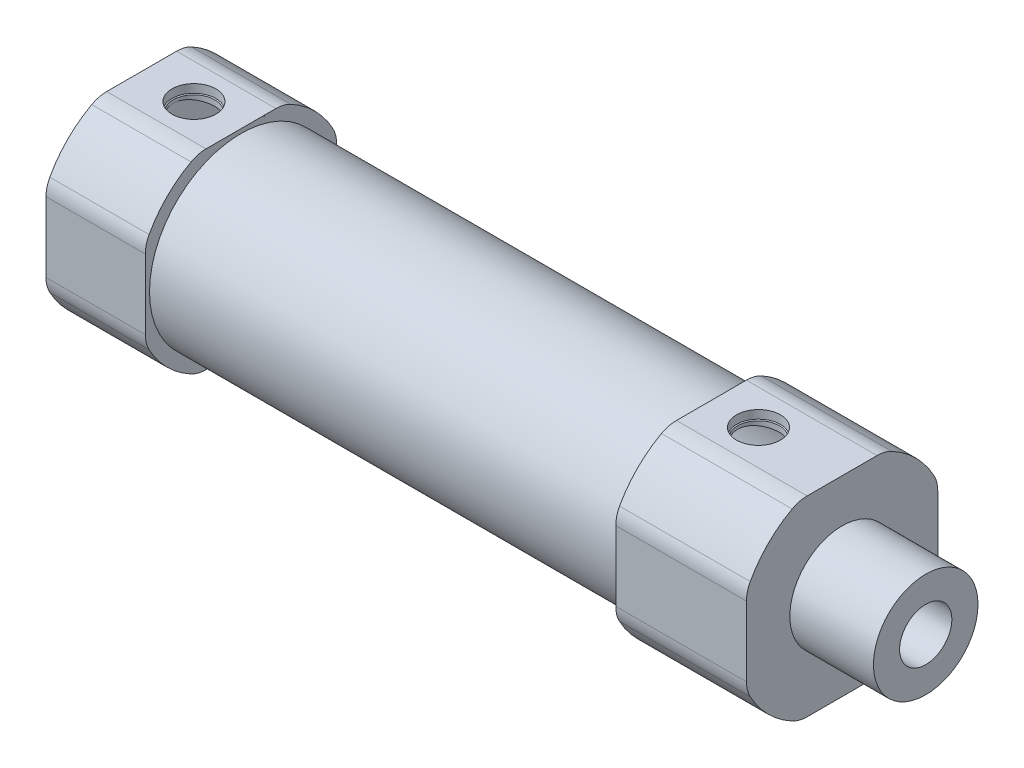
SolidWorks part; units mm, degrees
material "6061-T6 (SS)"
ref_plane "前视基准面" through (0, 0, 0) normal (0, 0, 1) x (1, 0, 0)
ref_plane "上视基准面" through (0, 0, 0) normal (0, 1, 0) x (1, 0, 0)
ref_plane "右视基准面" through (0, 0, 0) normal (1, 0, 0) x (0, 0, -1)
sketch "主筒" plane through (0, 0, 0) normal (1, 0, 0) x (0, 0, -1)
  circle A0 centre (0, 0) radius 8.75
  dimension "D1" = 17.5
extrude "主缸筒" add sketch "主筒" along normal blind 67
sketch "前头1" plane through (67, 0, 0) normal (1, 0, 0) x (0, 0, -1)
  line L1 (-9.15, 9.15) -> (9.15, 9.15)
  line L2 (-9.15, 9.15) -> (-9.15, -9.15)
  line L3 (-9.15, -9.15) -> (9.15, -9.15)
  line L4 (9.15, 9.15) -> (9.15, -9.15)
  line L5 (-9.15, 9.15) -> (9.15, -9.15) construction
  line L6 (-9.15, -9.15) -> (9.15, 9.15) construction
  circle A0 centre (0, 0) radius 10
  point P0 (0, 0)
  circle M3 centre (0, 0) radius 8.75
  dimension "D2" = 20
  dimension "D1" = 18.3
extrude "前头" add sketch "前头1" against normal blind 12.5 contours L2 A0 L3 M3
sketch "后头1" plane through (0, 0, 0) normal (-1, 0, 0) x (0, 0, 1)
  line L1 (-9.15, 9.15) -> (9.15, 9.15)
  line L2 (-9.15, 9.15) -> (-9.15, -9.15)
  line L3 (-9.15, -9.15) -> (9.15, -9.15)
  line L4 (9.15, 9.15) -> (9.15, -9.15)
  line L5 (-9.15, 9.15) -> (9.15, -9.15) construction
  line L6 (-9.15, -9.15) -> (9.15, 9.15) construction
  circle A0 centre (0, 0) radius 10
  point P0 (0, 0)
  circle M9 centre (0, 0) radius 8.75
  dimension "D2" = 20
  dimension "D1" = 18.3
extrude "后头" add sketch "后头1" against normal blind 9.5 contours L4 A0 L1 L2 L3 M9
sketch "气管接头1" plane through (0, 9.15, 0) normal (0, 1, 0) x (1, 0, 0)
  line L0 (0, 0) -> (67, 0) construction
  line L1 (67, -4.0345) -> (67, 4.0345) construction
  line L2 (0, 4.0345) -> (0, -4.0345) construction
  circle A0 centre (5, 0) radius 2
  circle A1 centre (59, 0) radius 2
  dimension "D1" = 5
  dimension "D3" = 4
  dimension "D2" = 8
extrude "气管接头" cut sketch "气管接头1" against normal blind 10
hole_wizard "外孔" positions "3D草图1" profile "草图5" tap size "M5" standard "GB"
sketch3d "3D草图1"
  point P0 (5, 9.15, 0)
  point P3 (59, 9.15, 0)
sketch "草图5" plane through (5, 9.15, 0) normal (1, 0, 0) x (0, 0, 1)
  line L0 (0, 0) -> (0, 2.0618)
  line L1 (0, 2.0618) -> (2.1, 0.8)
  line L2 (2.1, 0.8) -> (2.1, 0)
  line L5 (2.1, 0) -> (0, 0)
  line L10 (0, 2.0618) -> (-2.1, 0.8) construction
  line L11 (0, -6.35) -> (0, 107.95) construction
  dimension "螺纹孔钻头直径" = 4.2
  dimension "螺纹孔钻头深度" = 0.8
  dimension "导头角度" = 118
cosmetic thread "孔螺蚊线1" parameters "D1"=0.8, "D2"=5
cosmetic thread "孔螺蚊线3" parameters "D1"=0.8, "D2"=5
sketch "内腔1" plane through (67, 0, 0) normal (1, 0, 0) x (0, 0, -1)
  circle A0 centre (0, 0) radius 8
  dimension "D1" = 16
extrude "切除-拉伸3" cut sketch "内腔1" against normal offset from surface (61 mm away) 3 from offset 3 up to face at (0, 0, 0) offset against normal yes
sketch "气缸头1" plane through (67, 0, 0) normal (1, 0, 0) x (0, 0, -1)
  circle A0 centre (0, 0) radius 5
  dimension "D1" = 10
extrude "气缸头" add sketch "气缸头1" along normal blind 8
cosmetic thread "装饰螺纹线1" parameters "D1"=5, "D2"=6.647
sketch "内芯1" plane through (75, 0, 0) normal (1, 0, 0) x (0, 0, -1)
  circle A0 centre (0, 0) radius 2.5
  dimension "D1" = 5
extrude "内芯" cut sketch "内芯1" against normal up to next
fillet "圆角2" radius 3 8 edges at (4.75, -4.0345, 9.15) (4.75, 4.0345, 9.15) (4.75, 4.0345, -9.15) (4.75, -4.0345, -9.15) (4.75, -9.15, -4.0345) (4.75, -9.15, 4.0345) (4.75, 9.15, 4.0345) (4.75, 9.15, -4.0345)
fillet "圆角3" radius 3 8 edges at (60.75, -4.0345, -9.15) (60.75, 4.0345, -9.15) (60.75, 9.15, -4.0345) (60.75, 9.15, 4.0345) (60.75, 4.0345, 9.15) (60.75, -4.0345, 9.15) (60.75, -9.15, 4.0345) (60.75, -9.15, -4.0345)
equation "\"行程l\"= 50"
equation "\"D1@主缸筒\"=\"行程l\"+47"
equation "\"行程2\"= 200"
